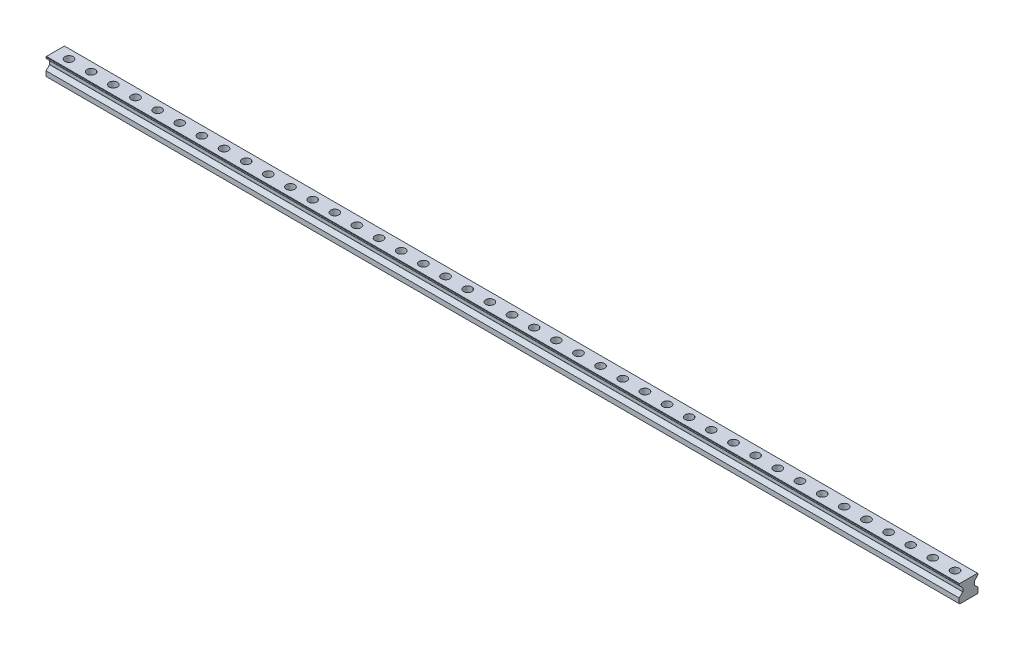
SolidWorks part; units mm, degrees
material "Low Carbon Steel"
ref_plane "Front Plane" through (0, 0, 0) normal (0, 0, 1) x (1, 0, 0)
ref_plane "Top Plane" through (0, 0, 0) normal (0, 1, 0) x (1, 0, 0)
ref_plane "Right Plane" through (0, 0, 0) normal (1, 0, 0) x (0, 0, -1)
sketch "Sketch2" plane through (0, 0, 0) normal (1, 0, 0) x (0, 0, -1)
  line L0 (10.6172, 22.7591) -> (17, 29.1419)
  line L1 (17, 29.1419) -> (17, 31.25)
  line L2 (17, 31.25) -> (16.25, 32)
  line L3 (16.25, 32) -> (-16.25, 32)
  line L4 (-16.25, 32) -> (-17, 31.25)
  line L5 (-17, 31.25) -> (-17, 29.1419)
  line L6 (-17, 29.1419) -> (-10.6172, 22.7591)
  line L7 (-10.5, 22.4762) -> (-10.5, 16.5238)
  line L8 (-10.6172, 16.2409) -> (-17, 9.8581)
  line L9 (-17, 9.8581) -> (-17, 1)
  line L10 (-17, 1) -> (-16, 0)
  line L11 (-16, 0) -> (16, 0)
  line L12 (16, 0) -> (17, 1)
  line L13 (17, 1) -> (17, 9.8581)
  line L14 (17, 9.8581) -> (10.6172, 16.2409)
  line L15 (10.5, 16.5238) -> (10.5, 22.4762)
  arc A0 (10.6172, 22.7591) -> (10.5, 22.4762) centre (10.9, 22.4762) ccw
  arc A1 (-10.5, 22.4762) -> (-10.6172, 22.7591) centre (-10.9, 22.4762) ccw
  arc A2 (-10.6172, 16.2409) -> (-10.5, 16.5238) centre (-10.9, 16.5238) ccw
  arc A3 (10.5, 16.5238) -> (10.6172, 16.2409) centre (10.9, 16.5238) ccw
extrude "Boss-Extrude2" add sketch "Sketch2" along normal mid plane 1649
hole_wizard "CBORE for M8 SHCS1" positions "Sketch4" profile "Sketch3" counterbore size "M8" standard "ANSI Metric" end condition through all
sketch "Sketch4" plane through (0, 32, 0) normal (0, 1, 0) x (-1, 0, 0)
  line L0 (-824.5, -16.25) -> (-824.5, 16.25) construction
  point P0 (-800, 0)
  point P4 (-824.5, 0)
  dimension "D1" = 24.5
sketch "Sketch3" plane through (800, 32, 0) normal (1, 0, 0) x (0, 0, 1)
  line L0 (0, 0) -> (0, 32)
  line L1 (0, 32) -> (4.5, 32)
  line L3 (4.5, 32) -> (4.5, 17)
  line L4 (4.5, 17) -> (7.5, 17)
  line L5 (7.5, 17) -> (7.5, 0)
  line L7 (7.5, 0) -> (0, 0)
  line L11 (0, -6.35) -> (0, 107.95) construction
  dimension "Thru Hole Dia." = 9
  dimension "Thru Hole Depth" = 32
  dimension "C'Bore Dia." = 15
  dimension "C'Bore Depth" = 17
pattern_linear "LPattern1" count 41 spacing 40 along (-1, 0, 0) of "CBORE for M8 SHCS1"
other "Freeze***"
